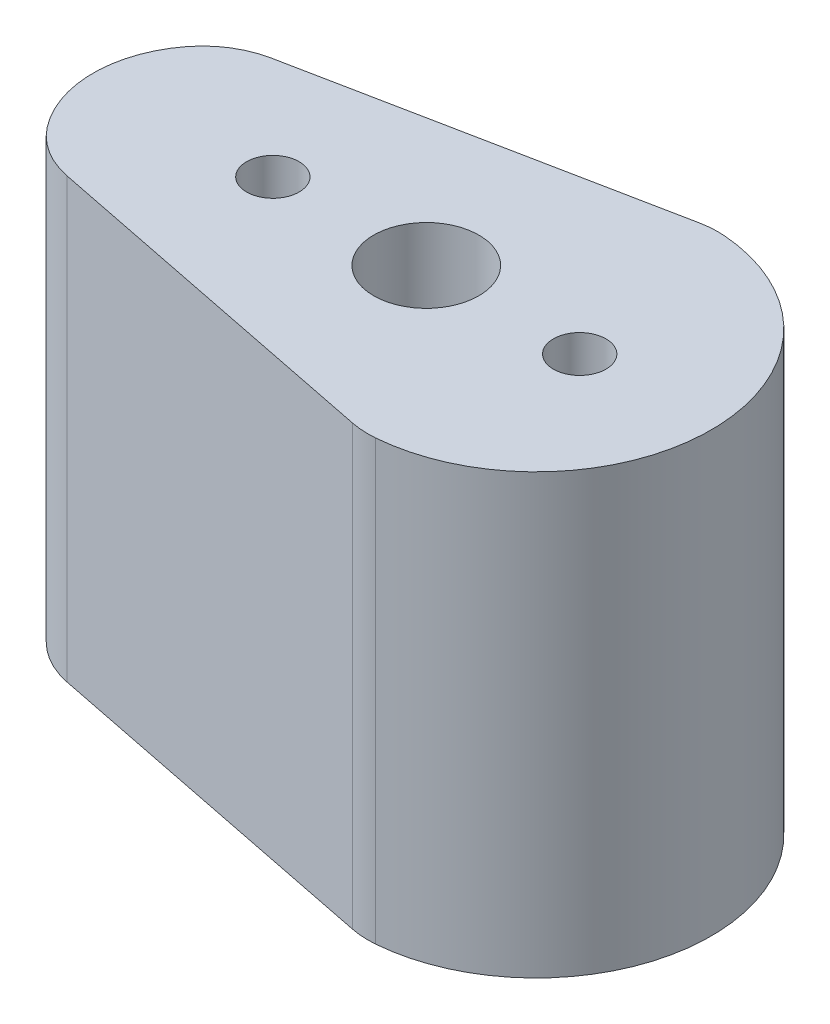
SolidWorks part; units mm, degrees
ref_plane "Front Plane" through (0, 0, 0) normal (0, 0, 1) x (1, 0, 0)
ref_plane "Top Plane" through (0, 0, 0) normal (0, 1, 0) x (1, 0, 0)
ref_plane "Right Plane" through (0, 0, 0) normal (1, 0, 0) x (0, 0, -1)
sketch "Sketch1" plane through (0, 0, 0) normal (0, 1, 0) x (1, 0, 0)
  line L0 (-0.1139, 1.9772) -> (-1.25, 1.7502)
  line L1 (-0.1139, -1.9772) -> (-1.25, -1.7502)
  line L4 (-1.25, -1.7502) -> (-4.1832, -1.1642)
  line L5 (-1.25, 1.7502) -> (-4.1832, 1.1642)
  circle A1 centre (-1.25, 0) radius 0.6
  arc A2 (0.1641, 1.9933) -> (0.1641, -1.9933) centre (0, 0) cw
  arc A3 (-0.1139, -1.9772) -> (0.1641, -1.9933) centre (0.0821, -0.9966) ccw
  arc A4 (-4.7783, 0.7954) -> (-4.7783, -0.7954) centre (-3.75, 0) ccw
  arc A5 (0.1641, 1.9933) -> (-0.1139, 1.9772) centre (0.0821, 0.9966) ccw
  arc A6 (-4.1832, 1.1642) -> (-4.7783, 0.7954) centre (-3.9873, 0.1835) ccw
  arc A7 (-4.1832, -1.1642) -> (-4.7783, -0.7954) centre (-3.9873, -0.1835) cw
  circle A8 centre (-3, 0) radius 0.3
  circle A9 centre (0.5, 0) radius 0.3
  point P12 (-3, 0)
  point P20 (0.5, 0)
extrude "Boss-Extrude1" add sketch "Sketch1" along normal blind 5
